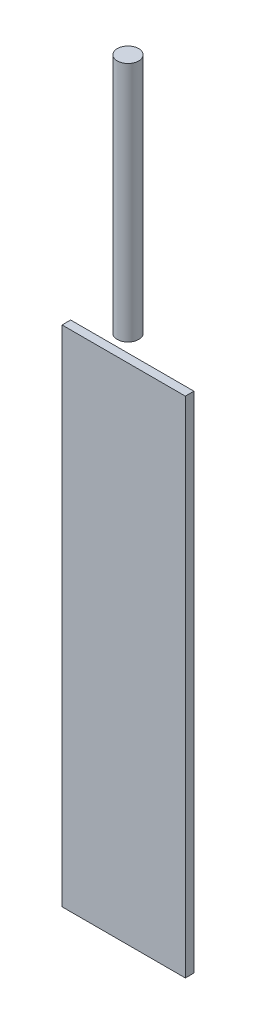
SolidWorks part; units mm, degrees
ref_plane "Front Plane" through (0, 0, 0) normal (0, 0, 1) x (1, 0, 0)
ref_plane "Top Plane" through (0, 0, 0) normal (0, 1, 0) x (1, 0, 0)
ref_plane "Right Plane" through (0, 0, 0) normal (1, 0, 0) x (0, 0, -1)
ref_plane "Plane1" through (0, 0, 25.2) normal (0, 0, 1) x (1, 0, 0)
sketch "Sketch1" plane through (0, 0, 25.2) normal (0, 0, 1) x (1, 0, 0)
  line L1 (8.5, -275.5) -> (31.5, -275.5)
  line L2 (8.5, -275.5) -> (8.5, -181.5)
  line L3 (8.5, -181.5) -> (31.5, -181.5)
  line L4 (31.5, -275.5) -> (31.5, -181.5)
  line L5 (8.5, -275.5) -> (31.5, -181.5) construction
  line L6 (8.5, -181.5) -> (31.5, -275.5) construction
  point P0 (20, -228.5)
extrude "Boss-Extrude1" add sketch "Sketch1" along normal blind 1.6
ref_plane "Plane2" through (0, -177.5, 0) normal (0, 1, 0) x (1, 0, 0)
sketch "Sketch2" plane through (0, -177.5, 0) normal (0, 1, 0) x (1, 0, 0)
  circle A0 centre (20, -26) radius 2
extrude "Boss-Extrude2" add sketch "Sketch2" along normal blind 45
